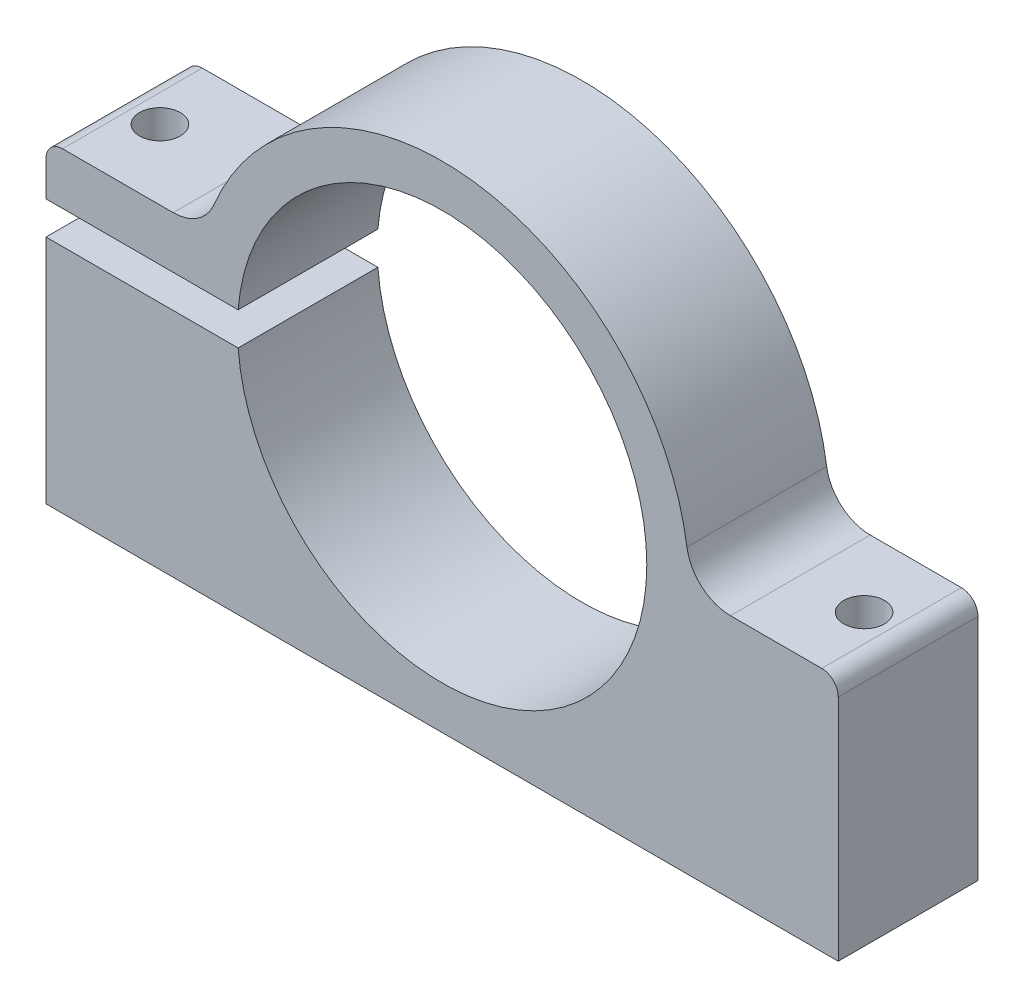
SolidWorks part; units mm, degrees
other "Defeature"
material "6061 Alloy"
ref_plane "Front Plane" through (0, 0, 0) normal (0, 0, 1) x (1, 0, 0)
ref_plane "Top Plane" through (0, 0, 0) normal (0, 1, 0) x (1, 0, 0)
ref_plane "Right Plane" through (0, 0, 0) normal (1, 0, 0) x (0, 0, -1)
sketch "Sketch1" plane through (0, 0, 0) normal (0, 0, 1) x (1, 0, 0)
  line L1 (0, -1.5) -> (-36, -1.5)
  line L2 (-36, -1.5) -> (-36, -22.5)
  line L3 (-36, -22.5) -> (36, -22.5)
  line L4 (36, -22.5) -> (36, -0.2)
  line L5 (36, -0.2) -> (22.4791, -0.2)
  line L7 (0, 1.5) -> (-36, 1.5)
  line L8 (-36, 1.5) -> (-36, 6.2)
  line L9 (-36, 6.2) -> (-21.6081, 6.2)
  line L10 (0, 1.5) -> (0, -1.5)
  arc A0 (22.4791, -0.2) -> (-21.6081, 6.2) centre (0, 0) ccw
  point P1 (0, -22.5)
  point P4 (0, 0)
  dimension "D1" = 44.96
  dimension "D2" = 72
  dimension "D3" = 3
  dimension "D4" = 21
  dimension "D6" = 36
  dimension "D8" = 28.7
  dimension "D9" = 22.3
extrude "Boss-Extrude1" add sketch "Sketch1" against normal mid plane 12.7 contours L1 L2 L3 L4 L5 A0 L9 L8 L7 L10
sketch "Sketch2" plane through (0, 0, 6.35) normal (0, 0, 1) x (1, 0, 0)
  circle A0 centre (0, 0) radius 18.6
  dimension "D1" = 37.2
extrude "Cut-Extrude1" cut sketch "Sketch2" against normal through all
sketch "Sketch5" plane through (0, 6.2, 0) normal (0, 1, 0) x (1, 0, 0)
  line L2 (-36, 6.35) -> (-36, -6.35) construction
  circle A0 centre (-32, 0) radius 1.85
  point P5 (-36, 0)
  dimension "D3" = 3.7
  dimension "D1" = 32
extrude "Cut-Extrude3" cut sketch "Sketch5" against normal through all
sketch "Sketch6" plane through (0, -0.2, 0) normal (0, 1, 0) x (1, 0, 0)
  line L1 (36, 6.35) -> (36, -6.35) construction
  circle A0 centre (32, 0) radius 1.85
  point P5 (36, 0)
  dimension "D1" = 3.7
  dimension "D2" = 32
extrude "Cut-Extrude4" cut sketch "Sketch6" against normal through all
fillet "Fillet2" radius 4 2 edges at (22.4791, -0.2, 0) (-21.6081, 6.2, 0)
fillet "Fillet6" radius 1.5 2 edges at (36, -0.2, 0) (-36, 6.2, 0)
